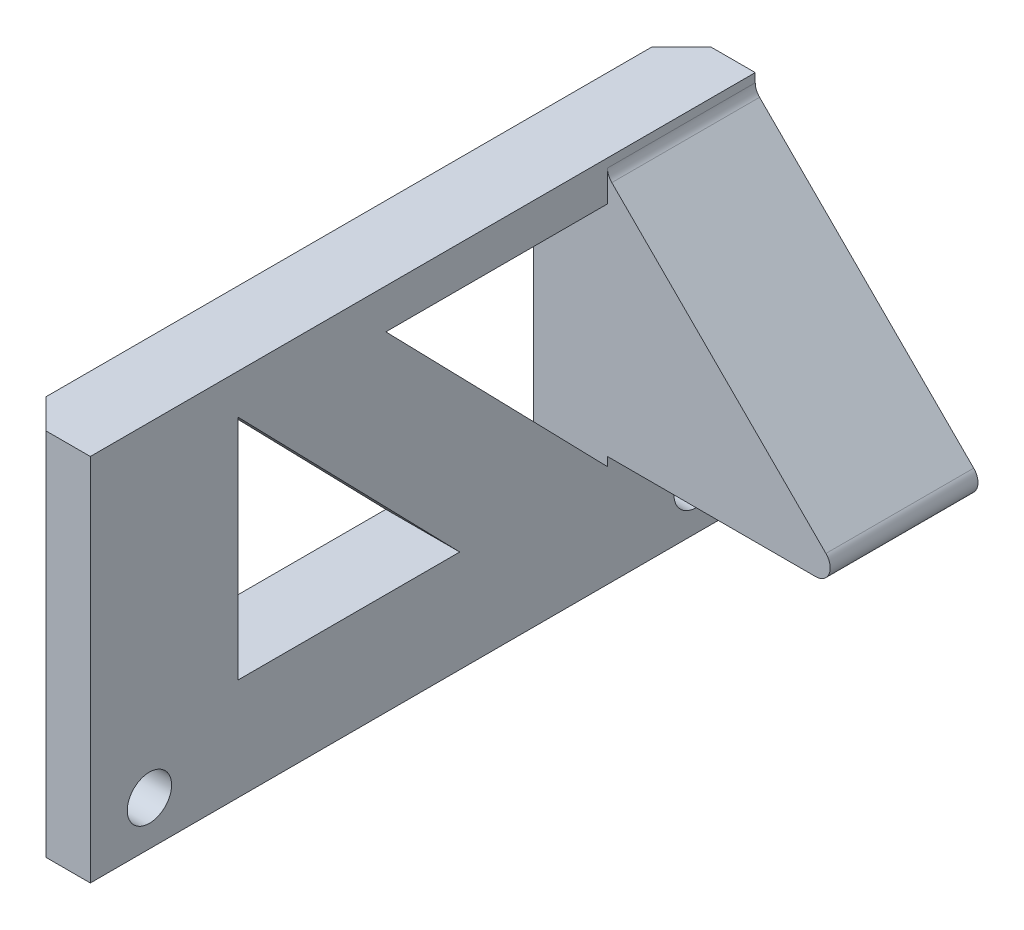
SolidWorks part; units mm, degrees
ref_plane "Front Plane" through (0, 0, 0) normal (0, 0, 1) x (1, 0, 0)
ref_plane "Top Plane" through (0, 0, 0) normal (0, 1, 0) x (1, 0, 0)
ref_plane "Right Plane" through (0, 0, 0) normal (1, 0, 0) x (0, 0, -1)
sketch "Sketch1" plane through (0, 0, 0) normal (1, 0, 0) x (0, 0, -1)
  line L1 (-22.5, 12.5) -> (22.5, 12.5)
  line L2 (-22.5, 12.5) -> (-22.5, -12.5)
  line L3 (-22.5, -12.5) -> (22.5, -12.5)
  line L4 (22.5, 12.5) -> (22.5, -12.5)
  line L5 (-22.5, 12.5) -> (22.5, -12.5) construction
  line L6 (-22.5, -12.5) -> (22.5, 12.5) construction
  point P0 (0, 0)
  dimension "D1" = 45
  dimension "D2" = 25
extrude "Boss-Extrude1" add sketch "Sketch1" along normal blind 5
sketch "Sketch2" plane through (5, 0, 0) normal (1, 0, 0) x (0, 0, -1)
  line L0 (-22.5, -12.5) -> (22.5, -12.5) construction
  circle A0 centre (-18.5, -9.5) radius 1.5
  circle A1 centre (18.5, -9.5) radius 1.5
  dimension "D2" = 3
  dimension "D3" = 3
  dimension "D1" = 37
  dimension "D4" = 18.5
  dimension "D5" = 3
  dimension "D6" = 3
extrude "Cut-Extrude1" cut sketch "Sketch2" against normal through all
sketch "Sketch3" plane through (5, 0, 0) normal (1, 0, 0) x (0, 0, -1)
  line L0 (-12.5, 9.8036) -> (-12.5, -5.5995)
  line L1 (-12.5, -5.5995) -> (2.5, -5.5995)
  line L2 (2.5, -5.5995) -> (-12.5, 9.8036)
  line L3 (-2.5, 9.8036) -> (12.5, 9.8036)
  line L4 (12.5, 9.8036) -> (12.5, -5.5995)
  line L6 (12.5, -5.5995) -> (-2.5, 9.8036)
  dimension "D1" = 15
  dimension "D2" = 15
extrude "Cut-Extrude2" cut sketch "Sketch3" against normal through all
chamfer "Chamfer2" distance 2 angle 45 2 edges at (0, 0, 22.5) (0, 0, -22.5)
sketch "Sketch4" plane through (0, 0, -22.5) normal (0, 0, -1) x (-1, 0, 0)
  line L0 (-5, -5) -> (-21.4903, -5)
  line L1 (-5, -12.5) -> (-5, 12.5) construction
  line L2 (-21.4903, -5) -> (-5, 11.4903)
  line L3 (-5, -12.5) -> (-2, -12.5) construction
  line L4 (-5, 11.4903) -> (-5, -5)
  dimension "D1" = 45
  dimension "D2" = 7.5
extrude "Boss-Extrude2" add sketch "Sketch4" against normal up to vertex
fillet "Fillet1" radius 1 2 edges at (21.4903, -5, -17.5) (5, 11.4903, -17.5)
